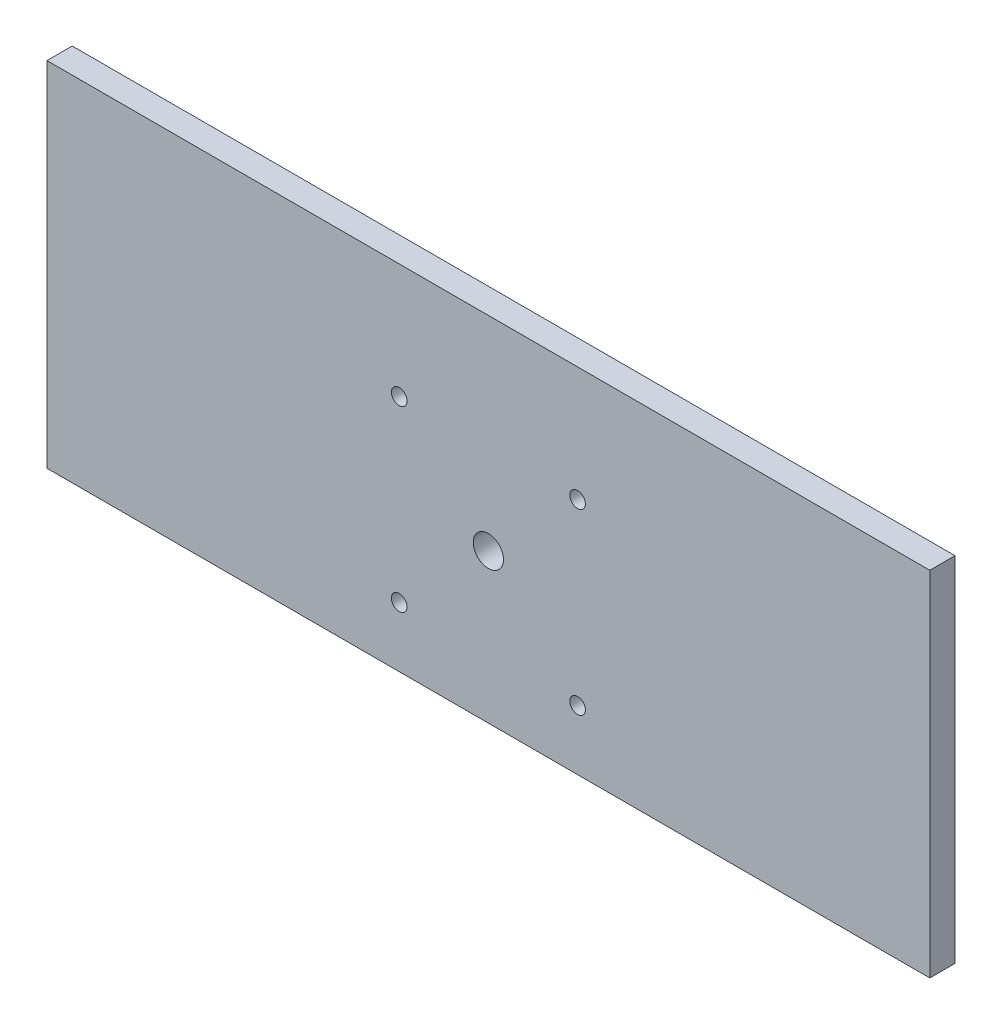
SolidWorks part; units mm, degrees
ref_plane "前视基准面" through (0, 0, 0) normal (0, 0, 1) x (1, 0, 0)
ref_plane "上视基准面" through (0, 0, 0) normal (0, 1, 0) x (1, 0, 0)
ref_plane "右视基准面" through (0, 0, 0) normal (1, 0, 0) x (0, 0, -1)
sketch "草图1" plane through (0, 0, 0) normal (0, 0, 1) x (1, 0, 0)
  line L2 (0, -25) -> (0, -95)
  line L3 (0, -95) -> (175, -95)
  line L4 (175, -25) -> (175, -95)
  line L6 (0, -25) -> (175, -25)
extrude "凸台-拉伸1" add sketch "草图1" along normal blind 5
sketch "草图2" plane through (0, 0, 5) normal (0, 0, 1) x (1, 0, 0)
  circle A0 centre (87.5, -65.45) radius 3
  circle A1 centre (69.8223, -47.7723) radius 1.55
  circle A2 centre (105.1777, -47.7723) radius 1.55
  circle A3 centre (105.1777, -83.1277) radius 1.55
  circle A4 centre (69.8223, -83.1277) radius 1.55
extrude "切除-拉伸1" cut sketch "草图2" against normal blind 10
